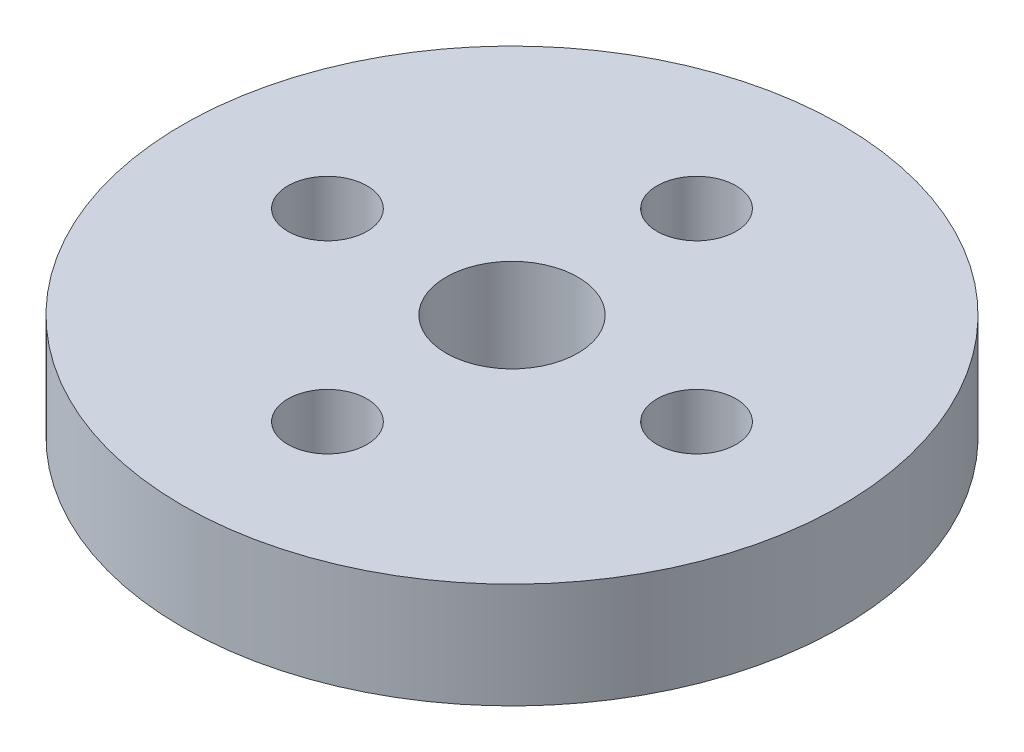
SolidWorks part; units mm, degrees
ref_plane "前视基准面" through (0, 0, 0) normal (0, 0, 1) x (1, 0, 0)
ref_plane "上视基准面" through (0, 0, 0) normal (0, 1, 0) x (1, 0, 0)
ref_plane "右视基准面" through (0, 0, 0) normal (1, 0, 0) x (0, 0, -1)
other "Configuration Table"
sketch "草图1" plane through (0, 0, 0) normal (0, 1, 0) x (1, 0, 0)
  line L0 (-7, 0) -> (0, 7) construction
  line L1 (-7, 0) -> (0, -7) construction
  line L2 (0, 7) -> (7, 0) construction
  line L3 (0, -7) -> (7, 0) construction
  line L4 (-7, 0) -> (7, 0) construction
  line L5 (0, 7) -> (0, -7) construction
  circle A0 centre (0, 0) radius 12.5
  circle A1 centre (0, 7) radius 1.5
  circle A2 centre (7, 0) radius 1.5
  circle A3 centre (0, -7) radius 1.5
  circle A4 centre (-7, 0) radius 1.5
  circle A5 centre (0, 0) radius 2.5
  dimension "D1" = 25
  dimension "D3" = 3
  dimension "D4" = 5
  dimension "D2" = 14
extrude "凸台-拉伸1" add sketch "草图1" along normal blind 4
